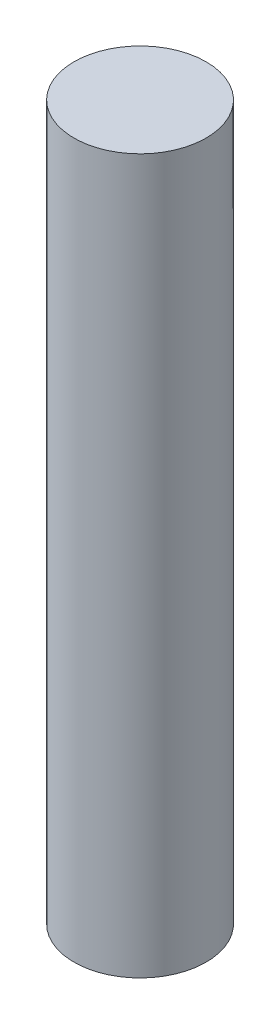
SolidWorks part; units mm, degrees
material "Stainless Steel (ferritic)"
ref_plane "Front Plane" through (0, 0, 0) normal (0, 0, 1) x (1, 0, 0)
ref_plane "Top Plane" through (0, 0, 0) normal (0, 1, 0) x (1, 0, 0)
ref_plane "Right Plane" through (0, 0, 0) normal (1, 0, 0) x (0, 0, -1)
sketch "Sketch1" plane through (0, 0, 0) normal (0, 1, 0) x (1, 0, 0)
  circle A0 centre (0, 0) radius 2
extrude "Boss-Extrude1" add sketch "Sketch1" along normal blind 21.6
